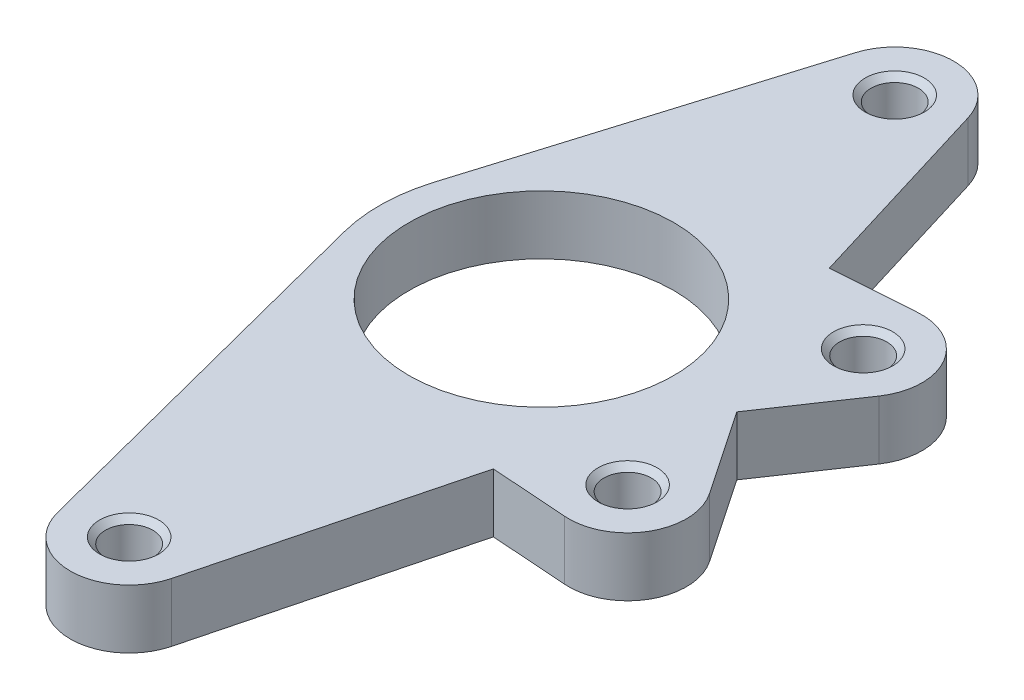
SolidWorks part; units mm, degrees
ref_plane "Front Plane" through (0, 0, 0) normal (0, 0, 1) x (1, 0, 0)
ref_plane "Top Plane" through (0, 0, 0) normal (0, 1, 0) x (1, 0, 0)
ref_plane "Right Plane" through (0, 0, 0) normal (1, 0, 0) x (0, 0, -1)
sketch "Sketch1" plane through (0, 0, 0) normal (0, 1, 0) x (1, 0, 0)
  line L0 (0, -38.1) -> (0, 38.1) construction
  line L1 (0, 0) -> (15.5234, 8.9624) construction
  line L2 (0, 0) -> (15.6955, -9.0618) construction
  line L3 (-16.7032, 5.0932) -> (-6.0739, 39.9521)
  line L4 (6.0739, 39.9521) -> (12.6448, 18.4029)
  line L5 (6.1484, -46.0375) -> (13.2721, -18.4473)
  line L6 (-6.1484, -46.0375) -> (-16.908, -4.3656)
  line L7 (27.258, 9.144) -> (21.0774, 0)
  line L8 (21.548, 19.0341) -> (12.6448, 18.4029)
  line L9 (-1.235, -17.4188) -> (0, -17.5063) construction
  line L10 (27.258, -9.144) -> (21.0774, 0)
  line L11 (0, -17.5063) -> (13.2721, -18.4473) construction
  line L12 (13.2721, -18.4473) -> (21.548, -19.0341)
  line L13 (13.2721, -18.4473) -> (15.6955, -9.0618) construction
  line L14 (16.1548, -7.2828) -> (16.908, -4.3656) construction
  line L15 (21.0774, 0) -> (16.1548, -7.2828) construction
  line L16 (16.1548, -7.2828) -> (15.1609, -8.7532) construction
  line L17 (21.0774, 0) -> (15.9376, 7.6041) construction
  line L18 (15.1609, 8.7532) -> (14.4676, 9.7789) construction
  line L19 (12.6448, 18.4029) -> (0, 17.5063) construction
  line L20 (0, 17.5063) -> (-1.235, 17.4188) construction
  line L21 (15.1609, -8.7532) -> (14.4676, -9.7789) construction
  line L22 (15.6955, -9.0618) -> (16.1548, -7.2828) construction
  line L23 (15.9376, 7.6041) -> (16.7032, 5.0932) construction
  line L24 (15.9376, 7.6041) -> (15.1609, 8.7532) construction
  line L25 (15.5234, 8.9624) -> (15.9376, 7.6041) construction
  line L26 (15.5234, 8.9624) -> (16.4978, 9.525) construction
  line L27 (16.4978, 9.525) -> (21.997, 12.7) construction
  line L28 (12.6448, 18.4029) -> (15.5234, 8.9624) construction
  line L29 (15.6955, -9.0618) -> (16.4978, -9.525) construction
  line L30 (16.4978, -9.525) -> (21.997, -12.7) construction
  line L31 (0, -44.45) -> (0, -38.1) construction
  arc A0 (-16.7032, 5.0932) -> (-16.908, -4.3656) centre (0, 0) ccw
  arc A1 (6.0739, 39.9521) -> (-6.0739, 39.9521) centre (0, 38.1) ccw
  arc A2 (-6.1484, -46.0375) -> (6.1484, -46.0375) centre (0, -44.45) ccw
  arc A3 (27.258, 9.144) -> (21.548, 19.0341) centre (21.997, 12.7) ccw
  arc A4 (21.548, -19.0341) -> (27.258, -9.144) centre (21.997, -12.7) ccw
  circle A5 centre (0, 0) radius 14.2875
  arc A6 (-1.235, 17.4188) -> (-16.7032, 5.0932) centre (0, 0) ccw construction
  arc A7 (14.4676, 9.7789) -> (0, 17.4625) centre (0, 0) ccw construction
  arc A8 (0, 17.4625) -> (-1.235, 17.4188) centre (0, 0) ccw construction
  arc A9 (16.908, -4.3656) -> (16.7032, 5.0932) centre (0, 0) ccw construction
  arc A10 (15.123, 8.7312) -> (14.4676, 9.7789) centre (0, 0) ccw construction
  arc A11 (16.7032, 5.0932) -> (15.123, 8.7312) centre (0, 0) ccw construction
  arc A12 (0, -17.4625) -> (14.4676, -9.7789) centre (0, 0) ccw construction
  arc A13 (14.4676, -9.7789) -> (15.123, -8.7313) centre (0, 0) ccw construction
  arc A14 (15.123, -8.7313) -> (16.908, -4.3656) centre (0, 0) ccw construction
  arc A15 (-16.908, -4.3656) -> (-1.235, -17.4188) centre (0, 0) ccw construction
  arc A16 (-1.235, -17.4188) -> (0, -17.4625) centre (0, 0) ccw construction
  arc A17 (0, 31.75) -> (6.0739, 39.9521) centre (0, 38.1) ccw construction
  arc A18 (-6.0739, 39.9521) -> (0, 31.75) centre (0, 38.1) ccw construction
  arc A19 (16.4978, 9.525) -> (27.258, 9.144) centre (21.997, 12.7) ccw construction
  arc A20 (21.548, 19.0341) -> (16.4978, 9.525) centre (21.997, 12.7) ccw construction
  arc A21 (16.4978, -9.525) -> (21.548, -19.0341) centre (21.997, -12.7) ccw construction
  arc A22 (27.258, -9.144) -> (16.4978, -9.525) centre (21.997, -12.7) ccw construction
  arc A23 (0, -38.1) -> (-6.1484, -46.0375) centre (0, -44.45) ccw construction
  arc A24 (6.1484, -46.0375) -> (0, -38.1) centre (0, -44.45) ccw construction
  point P14 (0, 0)
  dimension "D1" = 34.925
  dimension "D6" = 12.7
  dimension "D8" = 28.575
  dimension "D3" = 25.4
  dimension "D4" = 60
  dimension "D5" = 60
  dimension "D7" = 25.4
  dimension "D2" = 38.1
extrude "Boss-Extrude1" add sketch "Sketch1" along normal blind 6.35
sketch "Sketch2" plane through (0, 6.35, 0) normal (0, 1, 0) x (1, 0, 0)
  point P0 (0, -44.45)
  point P3 (21.997, -12.7)
  point P6 (21.997, 12.7)
  point P9 (0, 38.1)
hole_wizard "#10 Clearance Hole1" positions "Sketch2" profile "Sketch3" hole size "#10" standard "ANSI Inch" end condition up to next
sketch "Sketch3" plane through (0, 6.35, 44.45) normal (1, 0, 0) x (0, 0, 1)
  line L0 (0, 0) -> (0, 6.35)
  line L1 (0, 6.35) -> (3.1877, 6.35)
  line L2 (2.5527, 5.715) -> (2.5527, 0.635)
  line L3 (2.5527, 0.635) -> (3.1877, 0)
  line L5 (3.1877, 0) -> (0, 0)
  line L6 (-2.5527, 0.635) -> (-3.1877, 0) construction
  line L7 (3.1877, 6.35) -> (2.5527, 5.715)
  line L8 (-3.1877, 6.35) -> (-2.5527, 5.715) construction
  line L11 (0, -6.35) -> (0, 107.95) construction
  dimension "Thru Hole Dia." = 5.1054
  dimension "Thru Hole Depth" = 6.35
  dimension "Near C'Sink Dia." = 6.3754
  dimension "Near C'Sink Angle" = 90
  dimension "Far C'Sink Dia." = 6.3754
  dimension "Far C'Sink Angle" = 90
equation "\"D3@Sketch1\"=\"D7@Sketch1\""
